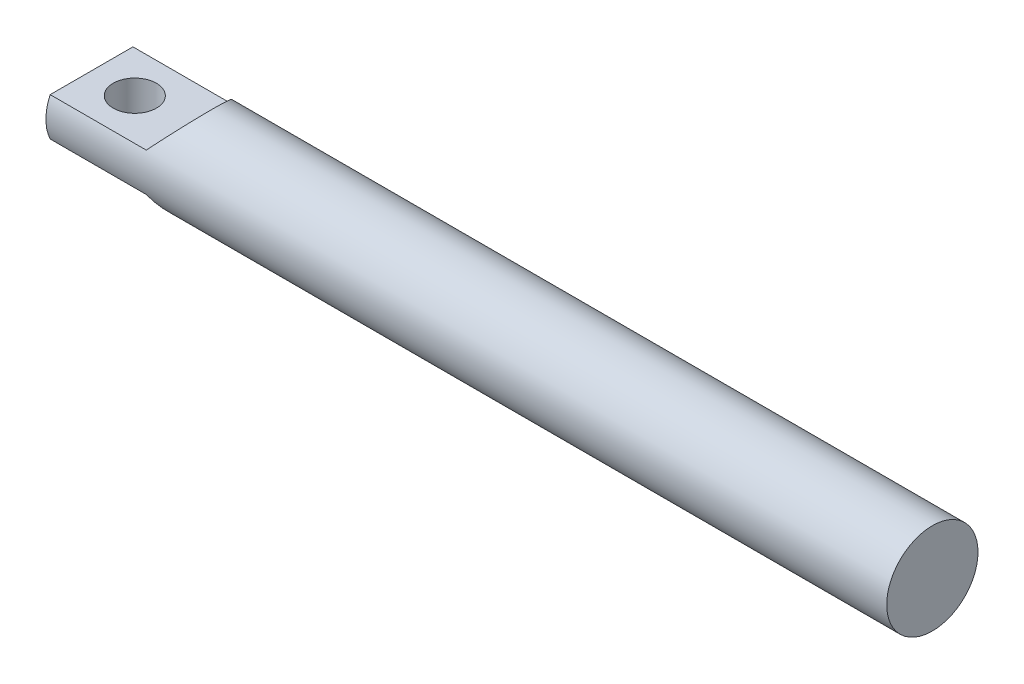
SolidWorks part; units mm, degrees
material "AISI 1020 Steel, Cold Rolled"
ref_plane "Front Plane" through (0, 0, 0) normal (0, 0, 1) x (1, 0, 0)
ref_plane "Top Plane" through (0, 0, 0) normal (0, 1, 0) x (1, 0, 0)
ref_plane "Right Plane" through (0, 0, 0) normal (1, 0, 0) x (0, 0, -1)
sketch "Sketch1" plane through (0, 0, 0) normal (1, 0, 0) x (0, 0, -1)
  circle A0 centre (0, 0) radius 9.5
extrude "Boss-Extrude1" add sketch "Sketch1" along normal blind 175
sketch "Sketch3" plane through (0, 0, 0) normal (0, 0, 1) x (1, 0, 0)
  line L4 (20, 4) -> (0, 4)
  line L6 (20, -4) -> (0, -4)
  line L9 (175, 9.5) -> (0, 9.5) construction
  line L10 (25, 9.5) -> (20, 4)
  line L12 (0, -9.5) -> (175, -9.5) construction
  line L13 (25, -9.5) -> (20, -4)
  line L14 (25, 9.5) -> (0, 9.5)
  line L15 (0, 9.5) -> (0, 4)
  line L17 (0, -4) -> (0, -9.5)
  line L18 (0, -9.5) -> (25, -9.5)
extrude "Cut-Extrude1" cut sketch "Sketch3" against normal through all both and the other way through all
sketch "Sketch4" plane through (0, 4, 0) normal (0, 1, 0) x (1, 0, 0)
  line L0 (0, 0) -> (9, 0)
  line L1 (0, -8.6168) -> (0, 8.6168) construction
  circle A0 centre (9, 0) radius 4.5
extrude "Cut-Extrude2" cut sketch "Sketch4" against normal through all
